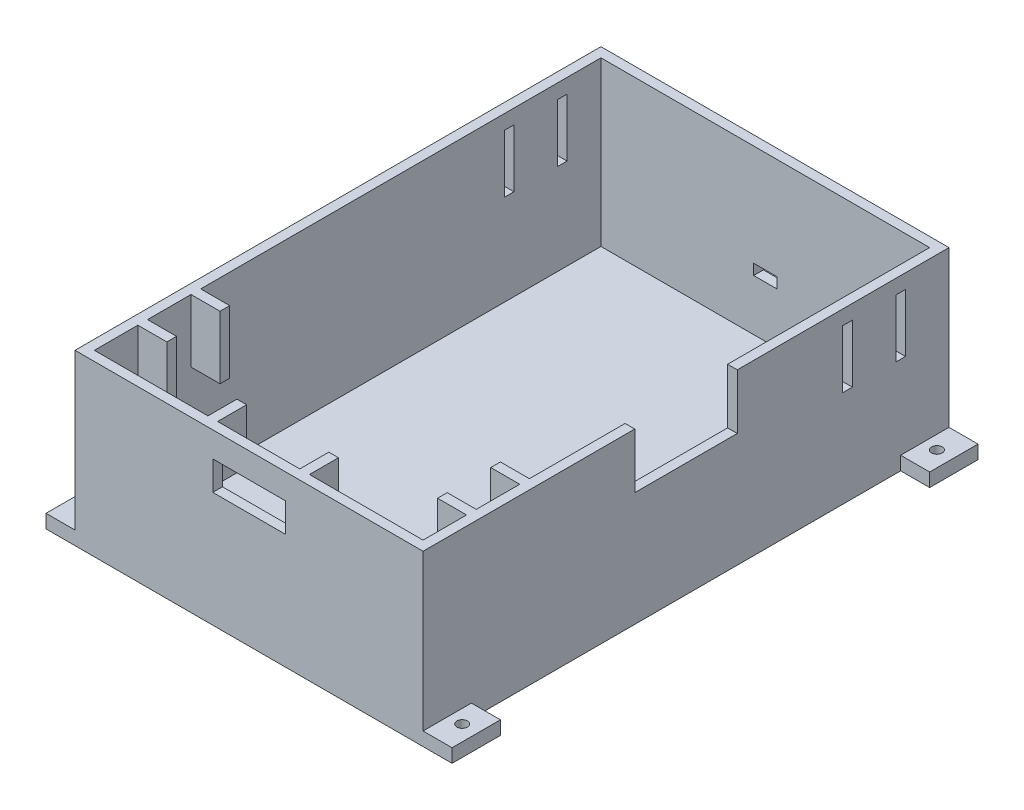
SolidWorks part; units mm, degrees
ref_plane "Plano frontal" through (0, 0, 0) normal (0, 0, 1) x (1, 0, 0)
ref_plane "Plano superior" through (0, 0, 0) normal (0, 1, 0) x (1, 0, 0)
ref_plane "Plano direito" through (0, 0, 0) normal (1, 0, 0) x (0, 0, -1)
sketch "Esboço1" plane through (0, 0, 0) normal (0, 1, 0) x (1, 0, 0)
  line L0 (-18, 27.2) -> (18, 27.2)
  line L1 (-17, 26.2) -> (17, 26.2)
  line L2 (-17, 26.2) -> (-17, -26.2)
  line L3 (-17, -26.2) -> (17, -26.2)
  line L4 (17, 26.2) -> (17, -26.2)
  line L5 (18, 27.2) -> (18, -27.2)
  line L6 (-18, -27.2) -> (18, -27.2)
  line L7 (-18, 27.2) -> (-18, -27.2)
  dimension "D1" = 52.4
  dimension "D2" = 34
  dimension "D3" = 17
  dimension "D4" = 26.2
  dimension "D5" = 1
extrude "Ressalto-extrusão1" add sketch "Esboço1" along normal blind 17
sketch "Esboço2" plane through (0, 0, 0) normal (0, 1, 0) x (1, 0, 0)
  line L1 (-17, -26.2) -> (17, -26.2)
  line L2 (-17, -26.2) -> (-17, 26.2)
  line L3 (-17, 26.2) -> (17, 26.2)
  line L4 (17, -26.2) -> (17, 26.2)
  line L5 (-17, -26.2) -> (17, 26.2) construction
  line L6 (-17, 26.2) -> (17, -26.2) construction
  point P0 (0, 0)
extrude "Ressalto-extrusão2" add sketch "Esboço2" along normal blind 0.1
sketch "Esboço3" plane through (0, 0, 27.2) normal (0, 0, 1) x (1, 0, 0)
  line L1 (-3.75, 14.4) -> (3.75, 14.4)
  line L2 (-3.75, 14.4) -> (-3.75, 11.4)
  line L3 (-3.75, 11.4) -> (3.75, 11.4)
  line L4 (3.75, 14.4) -> (3.75, 11.4)
  dimension "D1" = 14.4
  dimension "D2" = 7.5
  dimension "D3" = 3
  dimension "D4" = 3.75
extrude "Corte-extrusão1" cut sketch "Esboço3" against normal mid plane 11
sketch "Esboço4" plane through (0, 0, -26.2) normal (0, 0, 1) x (1, 0, 0)
  line L5 (-1.2, 5.4) -> (1.2, 5.4)
  line L6 (-1.2, 5.4) -> (-1.2, 6.5)
  line L7 (-1.2, 6.5) -> (1.2, 6.5)
  line L8 (1.2, 5.4) -> (1.2, 6.5)
  dimension "D1" = 2.4
  dimension "D2" = 1.2
  dimension "D3" = 1.1
  dimension "D4" = 5.4
extrude "Corte-extrusão2" cut sketch "Esboço4" against normal mid plane 11
sketch "Esboço5" plane through (0, 0, 0) normal (0, 1, 0) x (1, 0, 0)
  line L1 (18, -27.2) -> (21, -27.2)
  line L2 (18, -27.2) -> (18, -22.2)
  line L3 (18, -22.2) -> (21, -22.2)
  line L4 (21, -27.2) -> (21, -22.2)
  line L5 (-18, -27.2) -> (-21, -27.2)
  line L6 (-18, -27.2) -> (-18, -22.2)
  line L7 (-18, -22.2) -> (-21, -22.2)
  line L8 (-21, -27.2) -> (-21, -22.2)
  line L9 (-18, 27.2) -> (-21, 27.2)
  line L10 (-18, 27.2) -> (-18, 22.2)
  line L11 (-18, 22.2) -> (-21, 22.2)
  line L12 (-21, 27.2) -> (-21, 22.2)
  line L13 (18, 27.2) -> (21, 27.2)
  line L14 (18, 27.2) -> (18, 22.2)
  line L15 (18, 22.2) -> (21, 22.2)
  line L16 (21, 27.2) -> (21, 22.2)
  circle A0 centre (-19.4, 24.55) radius 0.55
  circle A1 centre (19.4, 24.55) radius 0.55
  circle A2 centre (19.4, -24.55) radius 0.55
  circle A3 centre (-19.4, -24.55) radius 0.55
  dimension "D9" = 1.1
  dimension "D10" = 1.1
  dimension "D11" = 1.1
  dimension "D12" = 1.1
  dimension "D1" = 3
  dimension "D2" = 5
  dimension "D3" = 3
  dimension "D4" = 5
  dimension "D5" = 3
  dimension "D6" = 5
  dimension "D7" = 3
  dimension "D8" = 5
  dimension "D13" = 1.6
  dimension "D14" = 1.6
extrude "Ressalto-extrusão3" add sketch "Esboço5" along normal blind 0.9
sketch "Esboço7" plane through (18, 0, 0) normal (1, 0, 0) x (0, 0, -1)
  line L1 (5.3, 17) -> (-5.3, 17)
  line L2 (5.3, 17) -> (5.3, 11.3)
  line L3 (5.3, 11.3) -> (-5.3, 11.3)
  line L4 (-5.3, 17) -> (-5.3, 11.3)
  line L5 (5.3, 17) -> (-5.3, 11.3) construction
  line L6 (5.3, 11.3) -> (-5.3, 17) construction
  point P4 (0, 14.15)
  dimension "D2" = 10.6
  dimension "D1" = 17
  dimension "D5" = 5.7
  dimension "D6" = 5.3
extrude "Corte-extrusão3" cut sketch "Esboço7" against normal blind 3
sketch "Esboço8" plane through (17, 0, 0) normal (-1, 0, 0) x (0, 0, 1)
  line L0 (26.2, 17) -> (5.3, 17) construction
  line L1 (15.2, 10.5) -> (16.2, 10.5)
  line L2 (15.2, 10.5) -> (15.2, 17)
  line L3 (15.2, 17) -> (16.2, 17)
  line L4 (21.7, 10.5) -> (21.7, 17)
  line L5 (15.2, 10.5) -> (21.7, 17) construction
  line L6 (15.2, 17) -> (21.7, 10.5) construction
  line L8 (16.2, 17) -> (16.2, 10.5)
  line L10 (20.7, 17) -> (20.7, 10.5)
  line L11 (16.2, 17) -> (20.7, 10.5) construction
  line L12 (16.2, 10.5) -> (20.7, 17) construction
  line L13 (20.7, 10.5) -> (21.7, 10.5)
  line L14 (20.7, 17) -> (21.7, 17)
  point P0 (18.45, 13.75)
  point P5 (18.45, 13.75)
  dimension "D1" = 4.5
  dimension "D2" = 6.5
  dimension "D3" = 4.5
  dimension "D4" = 1
extrude "Ressalto-extrusão4" add sketch "Esboço8" along normal blind 3
sketch "Esboço9" plane through (-17, 0, 0) normal (1, 0, 0) x (0, 0, -1)
  line L4 (-21.7, 17) -> (-21.7, 10.5)
  line L5 (-20.7, 17) -> (-21.7, 17)
  line L6 (-20.7, 10.5) -> (-20.7, 17)
  line L7 (-21.7, 10.5) -> (-20.7, 10.5)
  line L8 (-21.7, 17) -> (-21.7, 10.5)
  line L9 (-20.7, 17) -> (-21.7, 17)
  line L10 (-20.7, 10.5) -> (-20.7, 17)
  line L11 (-21.7, 10.5) -> (-20.7, 10.5)
  line L12 (-16.2, 10.5) -> (-15.2, 10.5)
  line L13 (-16.2, 17) -> (-16.2, 10.5)
  line L14 (-15.2, 17) -> (-16.2, 17)
  line L15 (-15.2, 10.5) -> (-15.2, 17)
  line L16 (-16.2, 10.5) -> (-15.2, 10.5)
  line L17 (-16.2, 17) -> (-16.2, 10.5)
  line L18 (-15.2, 17) -> (-16.2, 17)
  line L19 (-15.2, 10.5) -> (-15.2, 17)
  dimension "D1" = 0
  dimension "D2" = 0
extrude "Ressalto-extrusão5" add sketch "Esboço9" along normal blind 3
sketch "Esboço10" plane through (0, 0, 26.2) normal (0, 0, -1) x (-1, 0, 0)
  line L1 (5.25, 11.4) -> (4.25, 11.4)
  line L2 (5.25, 11.4) -> (5.25, 17)
  line L4 (-5.25, 11.4) -> (-5.25, 17)
  line L6 (-3.75, 11.4) -> (3.75, 11.4) construction
  line L7 (4.25, 17) -> (4.25, 11.4)
  line L8 (-4.25, 17) -> (-4.25, 11.4)
  line L10 (-4.25, 11.4) -> (-5.25, 11.4)
  line L13 (18, 17) -> (-18, 17) construction
  line L14 (5.25, 17) -> (4.25, 17)
  line L15 (-4.25, 17) -> (-5.25, 17)
  dimension "D1" = 1
  dimension "D2" = 1
  dimension "D3" = 4.25
  dimension "D4" = 4.25
extrude "Ressalto-extrusão6" add sketch "Esboço10" along normal blind 3
sketch "Esboço11" plane through (0, 0, 0) normal (0, -1, 0) x (1, 0, 0)
  line L24 (-18, 22.2) -> (-18, -22.2)
  line L25 (-18, -22.2) -> (-21, -22.2)
  line L26 (-21, -22.2) -> (-21, -27.2)
  line L27 (-21, -27.2) -> (21, -27.2)
  line L28 (21, -27.2) -> (21, -22.2)
  line L29 (21, -22.2) -> (18, -22.2)
  line L30 (18, -22.2) -> (18, 22.2)
  line L31 (18, 22.2) -> (21, 22.2)
  line L32 (21, 22.2) -> (21, 27.2)
  line L33 (21, 27.2) -> (-21, 27.2)
  line L34 (-21, 27.2) -> (-21, 22.2)
  line L35 (-21, 22.2) -> (-18, 22.2)
  line L36 (-18, 22.2) -> (-18, -22.2)
  line L37 (-18, -22.2) -> (-21, -22.2)
  line L38 (-21, -22.2) -> (-21, -27.2)
  line L39 (-21, -27.2) -> (21, -27.2)
  line L40 (21, -27.2) -> (21, -22.2)
  line L41 (21, -22.2) -> (18, -22.2)
  line L42 (18, -22.2) -> (18, 22.2)
  line L43 (18, 22.2) -> (21, 22.2)
  line L44 (21, 22.2) -> (21, 27.2)
  line L45 (21, 27.2) -> (-21, 27.2)
  line L46 (-21, 27.2) -> (-21, 22.2)
  line L47 (-21, 22.2) -> (-18, 22.2)
  circle A0 centre (-19.4, -24.55) radius 0.55 construction
  circle A1 centre (19.4, -24.55) radius 0.55 construction
  circle A2 centre (19.4, 24.55) radius 0.55 construction
  circle A3 centre (-19.4, 24.55) radius 0.55 construction
  circle A4 centre (19.4, -24.55) radius 0.55
  circle A5 centre (19.4, 24.55) radius 0.55
  circle A6 centre (-19.4, 24.55) radius 0.55
  circle A7 centre (-19.4, -24.55) radius 0.55
  dimension "D1" = 0
extrude "Ressalto-extrusão7" add sketch "Esboço11" along normal blind 0.5
sketch "Esboço12" plane through (18, 0, 0) normal (1, 0, 0) x (0, 0, -1)
  line L0 (21.7, 15.5) -> (22.7, 15.5)
  line L2 (21.7, 15.5) -> (21.7, 9.5)
  line L3 (21.7, 9.5) -> (22.7, 9.5)
  line L4 (22.7, 15.5) -> (22.7, 9.5)
  line L8 (16.2, 15.5) -> (17.2, 15.5)
  line L9 (16.2, 15.5) -> (16.2, 9.5)
  line L10 (16.2, 9.5) -> (17.2, 9.5)
  line L11 (17.2, 15.5) -> (17.2, 9.5)
  point P3 (0, 0)
  point P4 (0, 0)
  point P7 (0, 0)
  point P11 (0, 0)
  dimension "D1" = 4.5
  dimension "D2" = 1
  dimension "D3" = 1
  dimension "D4" = 4.5
  dimension "D5" = 1.5
  dimension "D6" = 6
  dimension "D7" = 6
extrude "Corte-extrusão4" cut sketch "Esboço12" against normal blind 40
